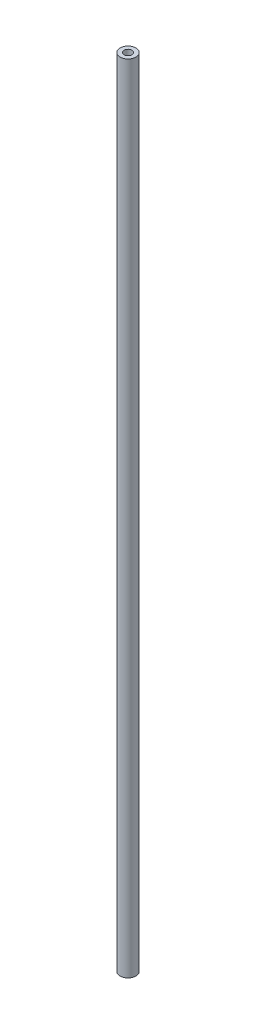
SolidWorks part; units mm, degrees
ref_plane "Alzado" through (0, 0, 0) normal (0, 0, 1) x (1, 0, 0)
ref_plane "Planta" through (0, 0, 0) normal (0, 1, 0) x (1, 0, 0)
ref_plane "Vista lateral" through (0, 0, 0) normal (1, 0, 0) x (0, 0, -1)
sketch "Croquis1" plane through (0, 0, 0) normal (0, 0, 1) x (1, 0, 0)
  line L0 (-1, 0) -> (-1, 200)
  line L1 (-1, 200) -> (-2, 200)
  line L2 (-2, 200) -> (-2, 0)
  line L3 (-2, 0) -> (-1, 0)
  line L4 (0, 0) -> (0, 6.2715) construction
  dimension "D1" = 4
  dimension "D2" = 2
  dimension "D3" = 200
revolve "Revolución1" add sketch "Croquis1" angle 360 about L4
